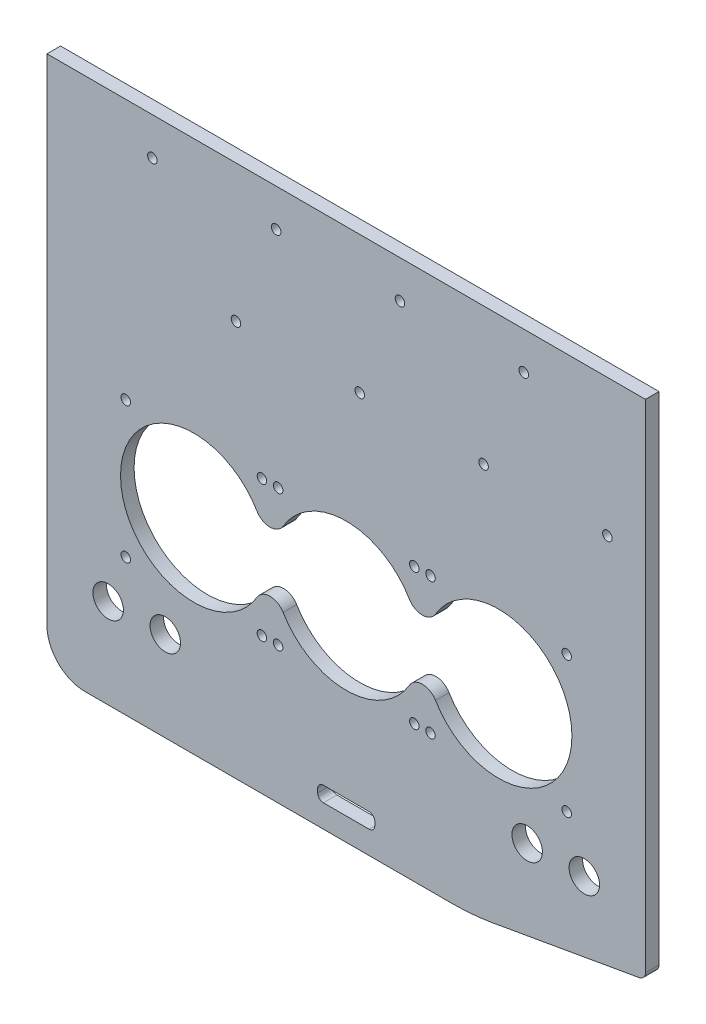
SolidWorks part; units mm, degrees
material "E-Glass Fiber"
ref_plane "Front Plane" through (0, 0, 0) normal (0, 0, 1) x (1, 0, 0)
ref_plane "Top Plane" through (0, 0, 0) normal (0, 1, 0) x (1, 0, 0)
ref_plane "Right Plane" through (0, 0, 0) normal (1, 0, 0) x (0, 0, -1)
sketch "Sketch1" plane through (0, 0, 0) normal (0, 0, -1) x (1, 0, 0)
  line L0 (0, -4.2398) -> (0, 81.0142) construction
  line L2 (0, -3.9116) -> (0, 3.9116) construction
  line L4 (-3381.666, 0) -> (-1328.9091, 0) construction
  line L5 (-157.112, -260) -> (-157.112, 20)
  line L6 (157.112, -260) -> (-157.112, -260)
  line L7 (157.112, -260) -> (157.112, 20)
  line L8 (157.112, 20) -> (-157.112, 20)
  line L10 (-3.9116, 0) -> (3.9116, 0) construction
  point P13 (0, -260)
  dimension "D1" = 314.224
  dimension "D2" = 280
  dimension "D3" = 20
extrude "Boss-Extrude1" add sketch "Sketch1" along normal blind 7.112
sketch "Sketch2" plane through (0, 0, 0) normal (0, 0, 1) x (1, 0, 0)
  line L0 (0, 127.612) -> (0, 47.612) construction
  line L1 (-120, 127.612) -> (120, 127.612) construction
  line L2 (-120, 127.612) -> (-120, 47.612) construction
  line L3 (-120, 47.612) -> (120, 47.612) construction
  line L4 (120, 127.612) -> (120, 47.612) construction
  line L5 (0, -3.9116) -> (0, 3.9116) construction
  line L6 (3.9116, 0) -> (-3.9116, 0) construction
  line L7 (0, 87.612) -> (-120, 87.612) construction
  line L8 (-120, 123.362) -> (0, 123.362) construction
  line L9 (-115.75, 127.612) -> (-115.75, 47.612) construction
  line L10 (-120, 51.862) -> (0, 51.862) construction
  line L11 (-44.25, 127.612) -> (-44.25, 47.612) construction
  line L12 (-35.75, 127.612) -> (-35.75, 47.612) construction
  arc A4 (33.1183, 107.2444) -> (-33.1183, 107.2444) centre (0, 87.612) ccw
  arc A5 (-46.8817, 107.2444) -> (-46.8817, 67.9796) centre (-80, 87.612) ccw
  arc A7 (-46.8817, 107.2444) -> (-33.1183, 107.2444) centre (-40, 111.3238) ccw
  arc A8 (33.1183, 67.9796) -> (-33.1183, 67.9796) centre (0, 87.612) cw
  arc A9 (-46.8817, 67.9796) -> (-33.1183, 67.9796) centre (-40, 63.9002) cw
  arc A10 (46.8817, 67.9796) -> (33.1183, 67.9796) centre (40, 63.9002) ccw
  arc A11 (46.8817, 107.2444) -> (46.8817, 67.9796) centre (80, 87.612) cw
  arc A12 (46.8817, 107.2444) -> (33.1183, 107.2444) centre (40, 111.3238) cw
  circle A13 centre (-115.75, 123.362) radius 2.5
  circle A14 centre (-44.25, 123.362) radius 2.5
  circle A17 centre (-35.75, 123.362) radius 2.5
  circle A19 centre (-115.75, 51.862) radius 2.5
  circle A20 centre (-44.25, 51.862) radius 2.5
  circle A21 centre (-35.75, 51.862) radius 2.5
  circle A22 centre (115.75, 51.862) radius 2.5
  circle A23 centre (44.25, 51.862) radius 2.5
  circle A24 centre (35.75, 51.862) radius 2.5
  circle A25 centre (35.75, 123.362) radius 2.5
  circle A26 centre (44.25, 123.362) radius 2.5
  circle A27 centre (115.75, 123.362) radius 2.5
  point P33 (-29.6586, 117.0883)
  point P34 (0, 0)
  point P49 (-21.0384, 47.612)
  point P50 (-29.0903, 127.612)
  point P51 (0, 0)
  dimension "D1" = 87.612
  dimension "D4" = 77
  dimension "D6" = 8
  dimension "D7" = 5
  dimension "D2" = 80
  dimension "D3" = 240
  dimension "D5" = 80
  dimension "D8" = 71.5
  dimension "D9" = 71.5
  dimension "D10" = 4.25
  dimension "D11" = 8.5
extrude "Cut-Extrude1" cut sketch "Sketch2" against normal through all
sketch "Sketch3" plane through (0, 0, 0) normal (0, 0, 1) x (1, 0, 0)
  line L0 (137.112, 188) -> (93.2255, 240.3018) construction
  line L1 (3.9116, 0) -> (-3.9116, 0) construction
  line L2 (157.112, 260) -> (157.112, -20) construction
  circle A0 centre (137.112, 188) radius 2.5
  circle A1 centre (93.2255, 240.3018) radius 2.5
  dimension "D3" = 5
  dimension "D1" = 50
  dimension "D2" = 20
  dimension "D4" = 188
  dimension "D5" = 68.2752
extrude "Cut-Extrude2" cut sketch "Sketch3" against normal offset from surface (6.731 mm away) 0.381 up to face at (46.75, 51.862, -7.112)
sketch "Sketch6" plane through (0, 0, -7.112) normal (0, 0, -1) x (-1, 0, 0)
  line L0 (0, 233.0482) -> (0, 127.2437) construction
  line L1 (0, 3.9116) -> (0, -3.9116) construction
  line L2 (-246.3493, 0) -> (-169.2336, 0) construction
  line L3 (3.9116, 0) -> (-3.9116, 0) construction
  line L4 (-125, 27.112) -> (-95, 27.112) construction
  circle A0 centre (-125, 27.112) radius 8
  circle A1 centre (-95, 27.112) radius 8
  circle A2 centre (95, 27.112) radius 8
  circle A3 centre (125, 27.112) radius 8
  dimension "D1" = 30
  dimension "D2" = 16
  dimension "D3" = 27.112
  dimension "D4" = 125
extrude "Cut-Extrude5" cut sketch "Sketch6" against normal through all
pattern_linear "LPattern1" count 4 spacing 65 along (-1, 0, 0) of "Cut-Extrude2"
sketch "Sketch4" plane through (0, 0, 0) normal (0, 0, 1) x (1, 0, 0)
  line L0 (-12, -8) -> (12, -8)
  line L1 (-15, -5) -> (-15, -3)
  line L2 (-12, 0) -> (12, 0)
  line L3 (0, 15.9368) -> (0, 30.4262) construction
  line L4 (15, -5) -> (15, -3)
  line L5 (0, -3.9116) -> (0, 3.9116) construction
  line L6 (3.9116, 0) -> (-3.9116, 0) construction
  arc A0 (-12, -8) -> (-15, -5) centre (-12, -5) cw
  arc A1 (-15, -3) -> (-12, 0) centre (-12, -3) cw
  arc A2 (15, -3) -> (12, 0) centre (12, -3) ccw
  arc A3 (12, -8) -> (15, -5) centre (12, -5) ccw
  point P1 (0, -8)
  point P15 (0, 0)
  dimension "D1" = 3
  dimension "D2" = 8
  dimension "D3" = 30
extrude "Cut-Extrude3" cut sketch "Sketch4" against normal through all
sketch "Sketch5" plane through (0, 0, 0) normal (0, 0, 1) x (1, 0, 0)
  line L0 (66.3715, -20) -> (157.112, -4)
  line L1 (157.112, -4) -> (157.112, -20)
  line L2 (157.112, -20) -> (66.3715, -20)
  line L3 (157.112, -20) -> (-157.112, -20) construction
  line L4 (157.112, 260) -> (157.112, -20) construction
  dimension "D1" = 10
  dimension "D2" = 16
extrude "Cut-Extrude4" cut sketch "Sketch5" against normal through all
fillet "Fillet1" radius 120 1 edges at (66.3715, -20, -3.556)
fillet "Fillet2" radius 20 1 edges at (-157.112, -20, -3.556)
fillet "Fillet3" radius 4 1 edges at (157.112, -4, -3.556)
